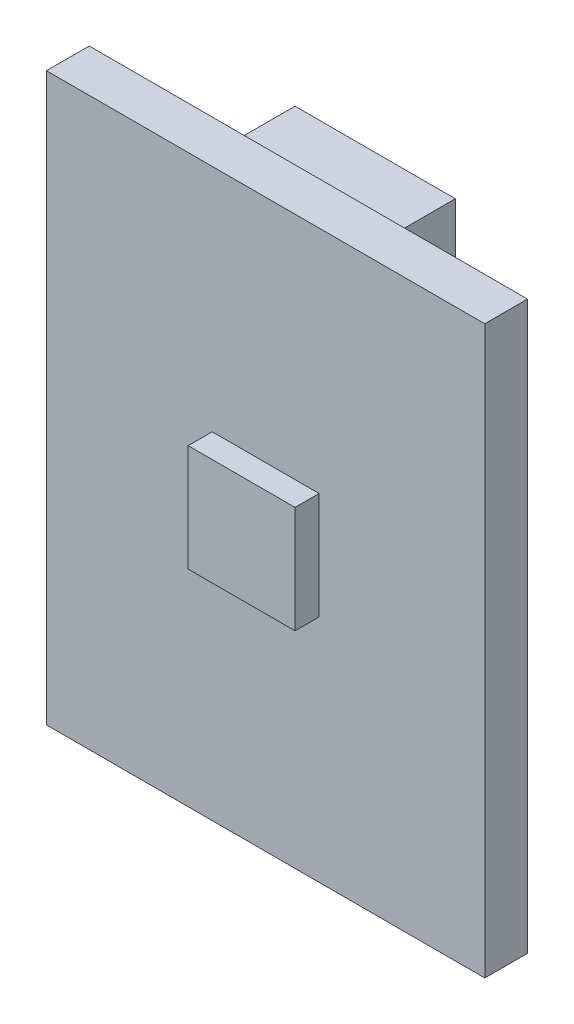
SolidWorks part; units mm, degrees
ref_plane "Front Plane" through (0, 0, 0) normal (0, 0, 1) x (1, 0, 0)
ref_plane "Top Plane" through (0, 0, 0) normal (0, 1, 0) x (1, 0, 0)
ref_plane "Right Plane" through (0, 0, 0) normal (1, 0, 0) x (0, 0, -1)
ref_plane "Plane1" through (0, 0, 13.1) normal (0, 0, 1) x (1, 0, 0)
sketch "Sketch1" plane through (0, 0, 13.1) normal (0, 0, 1) x (1, 0, 0)
  line L1 (13.8, -7.6) -> (30.2, -7.6)
  line L2 (13.8, -7.6) -> (13.8, 13.6)
  line L3 (13.8, 13.6) -> (30.2, 13.6)
  line L4 (30.2, -7.6) -> (30.2, 13.6)
  line L5 (13.8, -7.6) -> (30.2, 13.6) construction
  line L6 (13.8, 13.6) -> (30.2, -7.6) construction
  point P0 (22, 3)
extrude "Boss-Extrude1" add sketch "Sketch1" along normal blind 1.6
ref_plane "Plane2" through (0, 0, 10.6) normal (0, 0, 1) x (1, 0, 0)
sketch "Sketch2" plane through (0, 0, 10.6) normal (0, 0, 1) x (1, 0, 0)
  line L1 (19, -7) -> (25, -7)
  line L2 (19, -7) -> (19, 13)
  line L3 (19, 13) -> (25, 13)
  line L4 (25, -7) -> (25, 13)
  line L5 (19, -7) -> (25, 13) construction
  line L6 (19, 13) -> (25, -7) construction
  point P0 (22, 3)
extrude "Boss-Extrude2" add sketch "Sketch2" along normal blind 2.5
ref_plane "Plane3" through (0, 0, 14.7) normal (0, 0, 1) x (1, 0, 0)
sketch "Sketch3" plane through (0, 0, 14.7) normal (0, 0, 1) x (1, 0, 0)
  line L1 (20, 1) -> (24, 1)
  line L2 (20, 1) -> (20, 5)
  line L3 (20, 5) -> (24, 5)
  line L4 (24, 1) -> (24, 5)
  line L5 (20, 1) -> (24, 5) construction
  line L6 (20, 5) -> (24, 1) construction
  point P0 (22, 3)
extrude "Boss-Extrude3" add sketch "Sketch3" along normal blind 0.9
